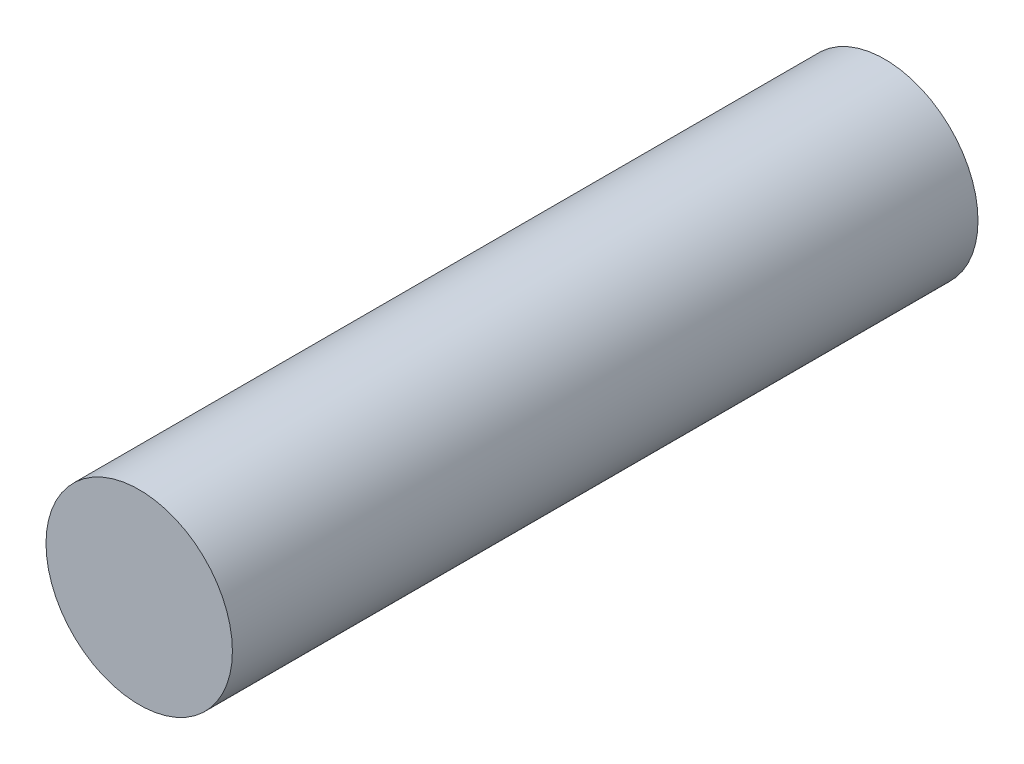
SolidWorks part; units mm, degrees
ref_plane "정면" through (0, 0, 0) normal (0, 0, 1) x (1, 0, 0)
ref_plane "윗면" through (0, 0, 0) normal (0, 1, 0) x (1, 0, 0)
ref_plane "우측면" through (0, 0, 0) normal (1, 0, 0) x (0, 0, -1)
sketch "스케치1" plane through (0, 0, 0) normal (0, 0, 1) x (1, 0, 0)
  circle A0 centre (0, 0) radius 3
  dimension "D1" = 6
extrude "보스-돌출1" add sketch "스케치1" along normal blind 24
